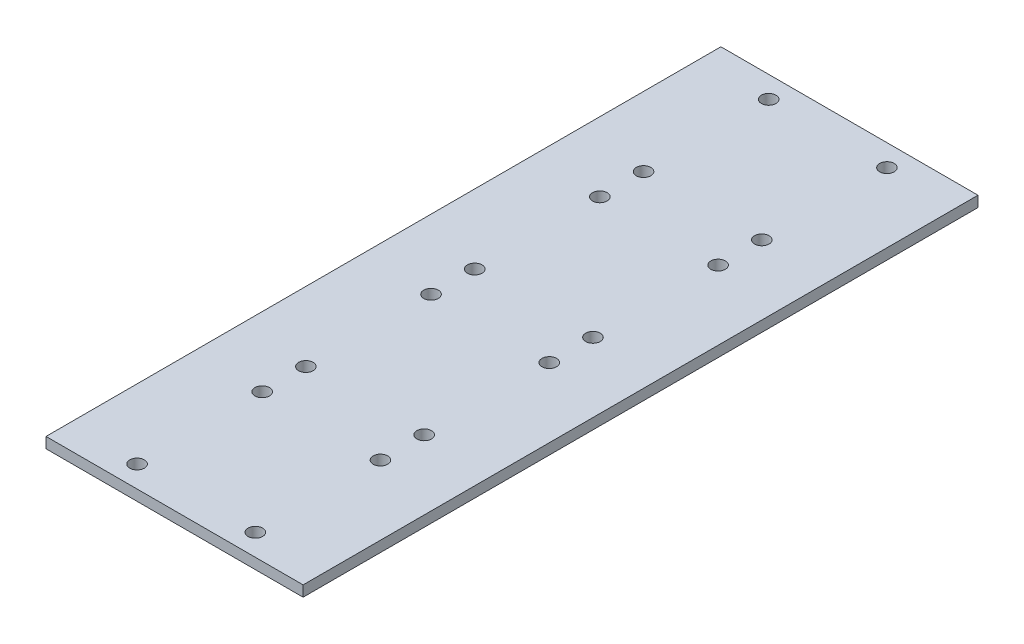
SolidWorks part; units mm, degrees
material "6061-T6 (SS)"
ref_plane "Front Plane" through (0, 0, 0) normal (0, 0, 1) x (1, 0, 0)
ref_plane "Top Plane" through (0, 0, 0) normal (0, 1, 0) x (1, 0, 0)
ref_plane "Right Plane" through (0, 0, 0) normal (1, 0, 0) x (0, 0, -1)
sketch "Sketch1" plane through (0, 0, 0) normal (0, 1, 0) x (1, 0, 0)
  line L0 (0, 0) -> (0, -37.084) construction
  line L1 (0, 0) -> (35.052, 0) construction
  line L2 (35.052, 0) -> (35.052, -37.084) construction
  line L3 (35.052, -37.084) -> (0, -37.084) construction
  line L4 (-20.574, 150.114) -> (0, 150.114) construction
  line L5 (-20.574, 156.5275) -> (55.626, 156.5275)
  line L6 (-20.574, 156.5275) -> (-20.574, -43.4975)
  line L7 (-20.574, -43.4975) -> (55.626, -43.4975)
  line L8 (55.626, 156.5275) -> (55.626, -43.4975)
  line L9 (0, 50.038) -> (35.052, 50.038) construction
  line L10 (0, 50.038) -> (0, 12.954) construction
  line L11 (0, 12.954) -> (35.052, 12.954) construction
  line L12 (35.052, 50.038) -> (35.052, 12.954) construction
  line L13 (0, 100.076) -> (35.052, 100.076) construction
  line L14 (0, 100.076) -> (0, 62.992) construction
  line L15 (0, 62.992) -> (35.052, 62.992) construction
  line L16 (35.052, 100.076) -> (35.052, 62.992) construction
  line L17 (0, 150.114) -> (35.052, 150.114) construction
  line L18 (0, 150.114) -> (0, 113.03) construction
  line L19 (0, 113.03) -> (35.052, 113.03) construction
  line L20 (35.052, 150.114) -> (35.052, 113.03) construction
  line L21 (35.052, 150.114) -> (55.626, 150.114) construction
  line L22 (0, 150.114) -> (0, 156.5275) construction
  line L23 (0, -37.084) -> (0, -43.4975) construction
  circle A0 centre (0, 0) radius 2.159
  circle A1 centre (35.052, 0) radius 2.159
  circle A2 centre (0, -37.084) radius 2.159
  circle A3 centre (35.052, -37.084) radius 2.159
  circle A6 centre (0, 50.038) radius 2.159
  circle A7 centre (35.052, 50.038) radius 2.159
  circle A8 centre (0, 12.954) radius 2.159
  circle A9 centre (35.052, 12.954) radius 2.159
  circle A10 centre (0, 100.076) radius 2.159
  circle A11 centre (35.052, 100.076) radius 2.159
  circle A12 centre (0, 62.992) radius 2.159
  circle A13 centre (35.052, 62.992) radius 2.159
  circle A14 centre (0, 150.114) radius 2.159
  circle A15 centre (35.052, 150.114) radius 2.159
  circle A16 centre (0, 113.03) radius 2.159
  circle A17 centre (35.052, 113.03) radius 2.159
  dimension "D1" = 4.318
  dimension "D2" = 4.318
  dimension "D3" = 4.318
  dimension "D4" = 4.318
  dimension "D15" = 4.318
  dimension "D16" = 4.318
  dimension "D13" = 4.318
  dimension "D14" = 4.318
  dimension "D19" = 4.318
  dimension "D20" = 4.318
  dimension "D21" = 4.318
  dimension "D22" = 4.318
  dimension "D25" = 4.318
  dimension "D26" = 4.318
  dimension "D27" = 4.318
  dimension "D28" = 4.318
  dimension "D5" = 35.052
  dimension "D6" = 35.052
  dimension "D7" = 37.084
  dimension "D8" = 37.084
  dimension "D9" = 12.954
  dimension "D10" = 12.954
  dimension "D11" = 12.954
  dimension "D12" = 200.025
  dimension "D17" = 37.084
  dimension "D18" = 35.052
  dimension "D23" = 35.052
  dimension "D24" = 37.084
  dimension "D29" = 37.084
  dimension "D30" = 35.052
  dimension "D31" = 76.2
extrude "Boss-Extrude1" add sketch "Sketch1" along normal blind 3.175
